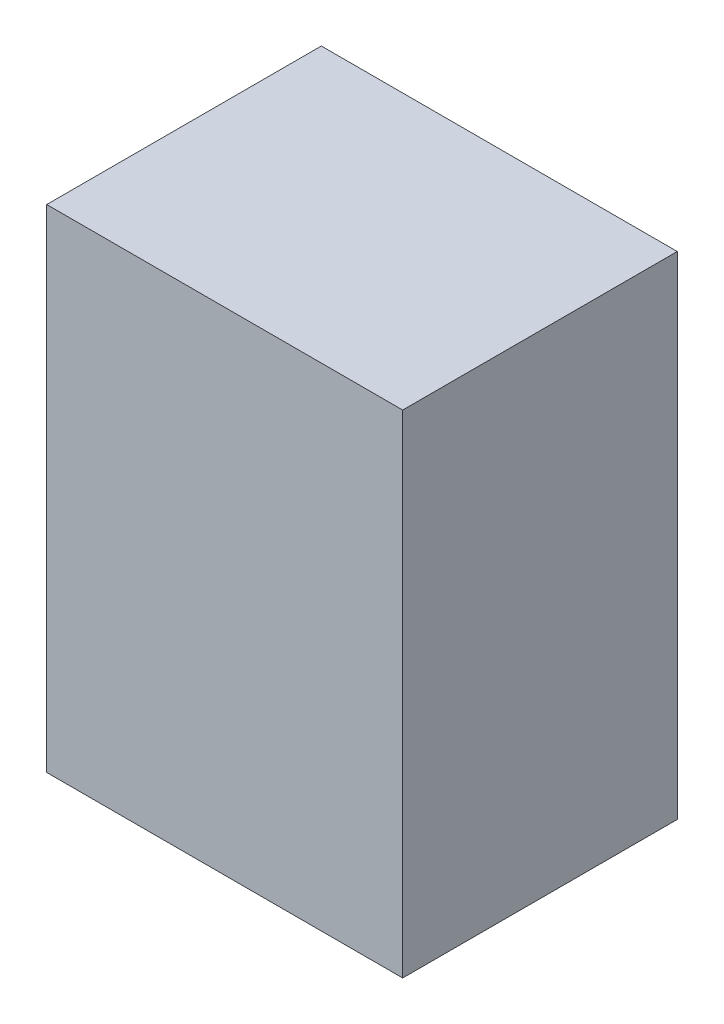
SolidWorks part; units mm, degrees
material "PE High Density"
ref_plane "Front Plane" through (0, 0, 0) normal (0, 0, 1) x (1, 0, 0)
ref_plane "Top Plane" through (0, 0, 0) normal (0, 1, 0) x (1, 0, 0)
ref_plane "Right Plane" through (0, 0, 0) normal (1, 0, 0) x (0, 0, -1)
sketch "Sketch1" plane through (0, 0, 0) normal (0, 1, 0) x (1, 0, 0)
  line L1 (-77.78, 60) -> (77.78, 60)
  line L2 (-77.78, 60) -> (-77.78, -60)
  line L3 (-77.78, -60) -> (77.78, -60)
  line L4 (77.78, 60) -> (77.78, -60)
  line L5 (-77.78, 60) -> (77.78, -60) construction
  line L6 (-77.78, -60) -> (77.78, 60) construction
  point P0 (0, 0)
  dimension "D1" = 155.56
  dimension "D2" = 120
extrude "Boss-Extrude1" add sketch "Sketch1" along normal blind 214.97
scale "Scale1" scale about centroid uniform scaling yes scale factor 0.75
